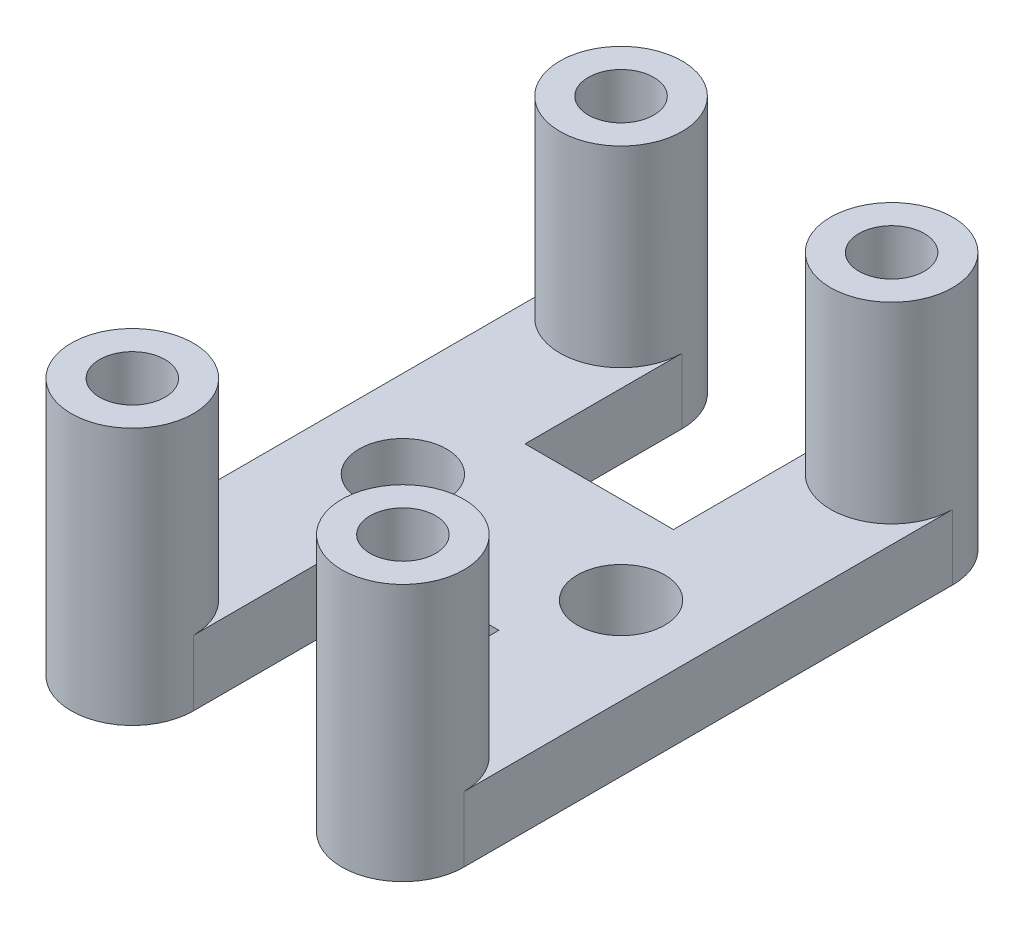
SolidWorks part; units mm, degrees
ref_plane "Front Plane" through (0, 0, 0) normal (0, 0, 1) x (1, 0, 0)
ref_plane "Top Plane" through (0, 0, 0) normal (0, 1, 0) x (1, 0, 0)
ref_plane "Right Plane" through (0, 0, 0) normal (1, 0, 0) x (0, 0, -1)
sketch "Sketch1" plane through (0, 0, 0) normal (0, 1, 0) x (1, 0, 0)
  line L0 (-2.8362, 5.08) -> (-2.0742, 5.08)
  line L2 (-2.0742, 5.08) -> (5.0378, 5.08)
  line L7 (1.4818, 17.78) -> (1.4818, -5.08) construction
  line L8 (-2.8362, -5.08) -> (5.7998, -5.08)
  line L9 (5.0378, 5.08) -> (5.7998, 5.08)
  line L11 (-12.2657, 0) -> (23.7269, 0) construction
  line L16 (-9.9482, -5.08) -> (-2.8362, -5.08)
  line L19 (-9.9482, -14.224) -> (-9.9482, 14.224)
  line L20 (-2.8362, 14.224) -> (-2.8362, 5.08)
  line L21 (12.9118, -14.224) -> (12.9118, 14.224)
  line L22 (5.7998, 14.224) -> (5.7998, 5.08)
  line L23 (5.7998, -14.224) -> (5.7998, -5.08)
  line L24 (-2.8362, -14.224) -> (-2.8362, -5.08)
  line L25 (5.7998, -5.08) -> (12.9118, -5.08)
  line L26 (5.7998, 5.08) -> (12.9118, 5.08)
  line L27 (-2.8362, 5.08) -> (-9.9482, 5.08)
  circle A0 centre (-4.8682, 0) radius 2.54
  circle A1 centre (7.8318, 0) radius 2.54
  arc A14 (-2.8362, 14.224) -> (-9.9482, 14.224) centre (-6.3922, 14.224) ccw
  circle A16 centre (-6.3922, 14.224) radius 1.905
  arc A17 (12.9118, 14.224) -> (5.7998, 14.224) centre (9.3558, 14.224) ccw
  circle A18 centre (9.3558, 14.224) radius 1.905
  circle A19 centre (9.3558, -14.224) radius 1.905
  arc A20 (12.9118, -14.224) -> (5.7998, -14.224) centre (9.3558, -14.224) cw
  arc A21 (-2.8362, -14.224) -> (-9.9482, -14.224) centre (-6.3922, -14.224) cw
  circle A22 centre (-6.3922, -14.224) radius 1.905
  circle A23 centre (-6.3922, 14.224) radius 3.556
  circle A24 centre (-6.3922, 14.224) radius 1.905
  circle A25 centre (9.3558, 14.224) radius 1.905
  circle A26 centre (9.3558, 14.224) radius 3.556
  circle A27 centre (-6.3922, -14.224) radius 1.905
  circle A28 centre (-6.3922, -14.224) radius 3.556
  circle A29 centre (9.3558, -14.224) radius 3.556
  circle A30 centre (9.3558, -14.224) radius 1.905
  point P40 (12.9118, 0)
  point P51 (-9.9482, 0)
  dimension "D4" = 7.112
  dimension "D5" = 3.81
  dimension "D6" = 7.112
  dimension "D7" = 3.81
extrude "Boss-Extrude1" add sketch "Sketch1" along normal blind 3.81
sketch "Sketch4" plane through (0, 3.81, 0) normal (0, 1, 0) x (1, 0, 0)
  circle A0 centre (-6.3922, 14.224) radius 1.905
  circle A1 centre (-6.3922, 14.224) radius 3.556
  circle A2 centre (9.3558, 14.224) radius 1.905
  circle A3 centre (9.3558, 14.224) radius 3.556
  circle A4 centre (9.3558, -14.224) radius 1.905
  circle A5 centre (9.3558, -14.224) radius 3.556
  circle A6 centre (-6.3922, -14.224) radius 1.905
  circle A7 centre (-6.3922, -14.224) radius 3.556
extrude "Boss-Extrude4" add sketch "Sketch4" along normal blind 11.176
